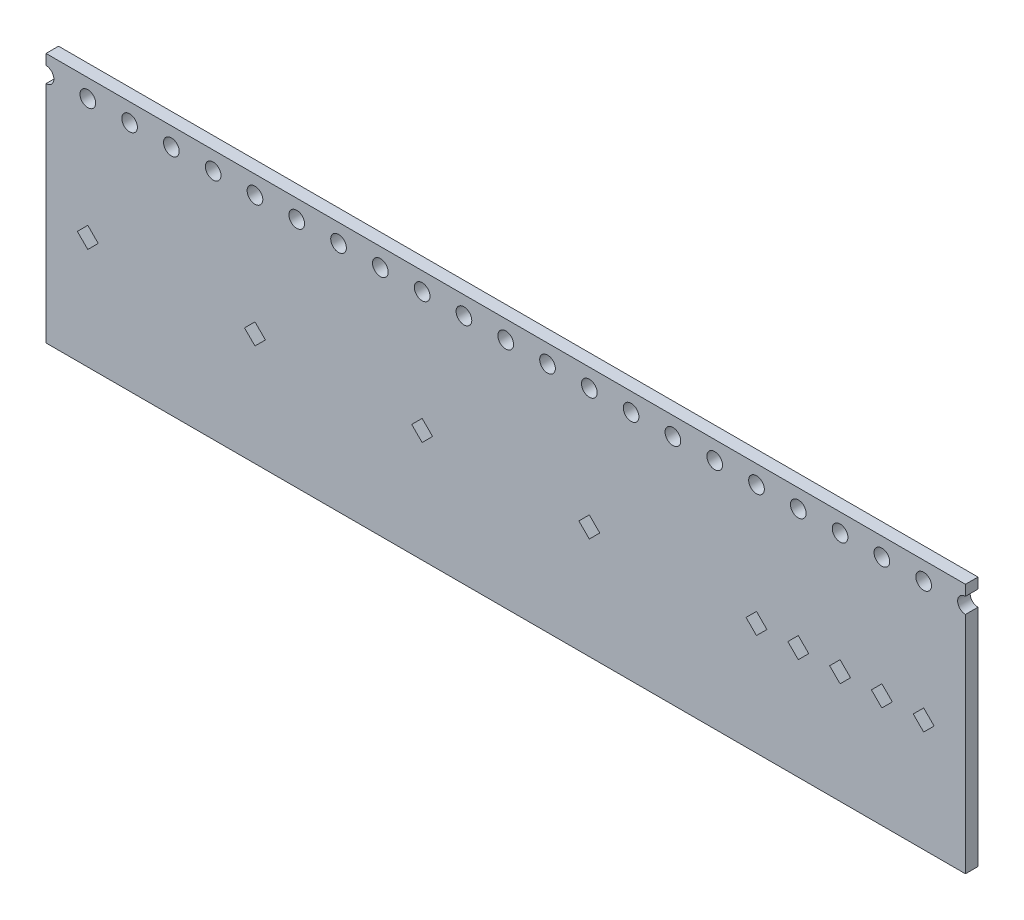
SolidWorks part; units mm, degrees
ref_plane "Top" through (0, 0, 0) normal (0, 0, 1) x (1, 0, 0)
ref_plane "Front" through (0, 0, 0) normal (0, 1, 0) x (1, 0, 0)
ref_plane "Right" through (0, 0, 0) normal (1, 0, 0) x (0, 0, -1)
sketch "Top Sketch" plane through (0, 0, 0) normal (0, 0, 1) x (1, 0, 0)
  line L1 (-88, 0) -> (0, 0)
  line L2 (-88, 0) -> (-88, -24)
  line L3 (-88, -24) -> (0, -24)
  line L4 (0, 0) -> (0, -24)
  dimension "Length" = 88
  dimension "Width" = 24
extrude "Thickness Extrude" add sketch "Top Sketch" against normal blind 1.2
sketch "Pin Hole Sketch" plane through (0, 0, 0) normal (0, 0, 1) x (1, 0, 0)
  line L0 (0, 0) -> (-88, 0) construction
  line L2 (0, -24) -> (0, 0) construction
  circle A0 centre (0, -1.75) radius 0.75
  dimension "D1" = 1.5
  dimension "D2" = 1.75
extrude "First Pin Hole Cut" cut sketch "Pin Hole Sketch" against normal through all
pattern_linear "Pin Hole Pattern" count 23 spacing 4 along (-1, 0, 0) of "First Pin Hole Cut"
sketch "Marker Sketch" plane through (0, 0, 0) normal (0, 0, 1) x (1, 0, 0)
  line L1 (-4, -12.25) -> (-5, -13.25)
  line L2 (-5, -13.25) -> (-3, -13.25) construction
  line L3 (-4, -3.25) -> (-4, -13.25) construction
  line L5 (-4, -1.75) -> (-4, -3.25) construction
  line L6 (-3, -13.25) -> (-4, -12.25)
  line L8 (-4, -14.25) -> (-5, -13.25)
  line L11 (-3, -13.25) -> (-4, -14.25)
  line L12 (0, 0) -> (-88, 0) construction
  dimension "Marker Position" = 13.25
extrude "Marker Cut" cut sketch "Marker Sketch" against normal through all
pattern_linear "Component Marker Pattern" count 4 spacing 4 along (-1, 0, 0) of "Marker Cut"
pattern_linear "Pin Hole Marker Pattern" count 6 spacing 16 along (-1, 0, 0) of "Marker Cut"
